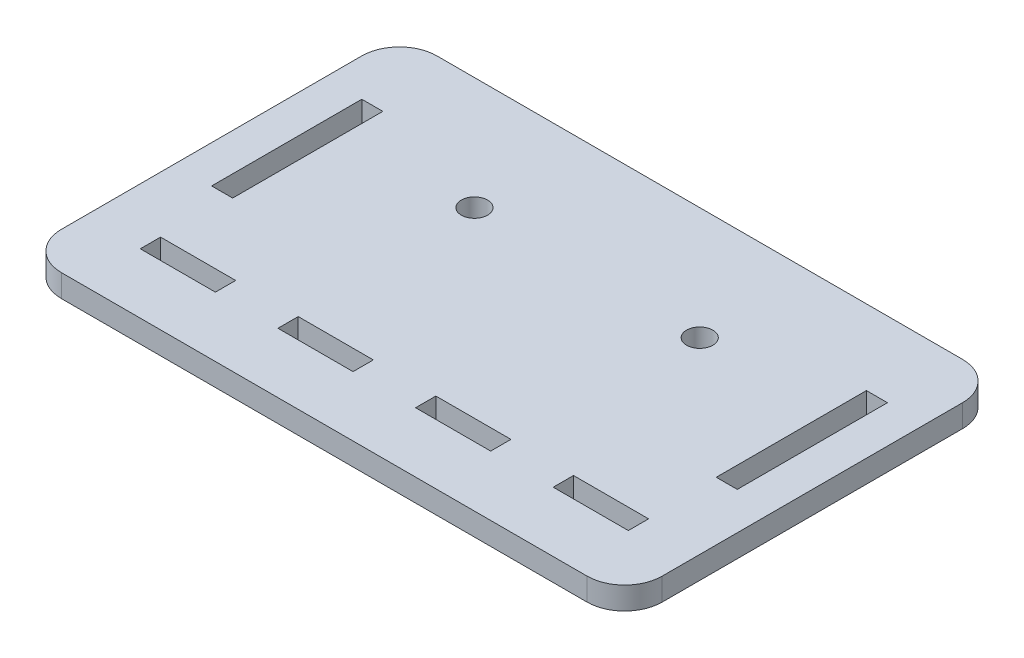
SolidWorks part; units mm, degrees
ref_plane "Front Plane" through (0, 0, 0) normal (0, 0, 1) x (1, 0, 0)
ref_plane "Top Plane" through (0, 0, 0) normal (0, 1, 0) x (1, 0, 0)
ref_plane "Right Plane" through (0, 0, 0) normal (1, 0, 0) x (0, 0, -1)
sketch "Sketch1" plane through (0, 0, 0) normal (0, 1, 0) x (1, 0, 0)
  line L0 (0, 35.9833) -> (0, -46.6527) construction
  line L1 (40, 25) -> (-40, 25)
  line L2 (-40, 25) -> (-40, -25)
  line L3 (-40, -25) -> (40, -25)
  line L4 (40, 25) -> (40, -25)
  line L5 (-32.5, -17) -> (32.5, -17) construction
  line L6 (-14.17, -14.3) -> (-4.17, -14.3)
  line L7 (-32.5, -17) -> (-22.5, -17)
  line L8 (-32.5, -17) -> (-32.5, -14.3)
  line L9 (-32.5, -14.3) -> (-22.5, -14.3)
  line L10 (-22.5, -17) -> (-22.5, -14.3)
  line L11 (-14.17, -17) -> (-4.17, -17)
  line L12 (-4.17, -17) -> (-4.17, -14.3)
  line L13 (-14.17, -17) -> (-14.17, -14.3)
  line L14 (4.16, -14.3) -> (14.16, -14.3)
  line L15 (4.16, -17) -> (14.16, -17)
  line L16 (14.16, -17) -> (14.16, -14.3)
  line L17 (4.16, -17) -> (4.16, -14.3)
  line L18 (22.49, -14.3) -> (32.49, -14.3)
  line L19 (22.49, -17) -> (32.49, -17)
  line L20 (32.49, -17) -> (32.49, -14.3)
  line L21 (22.49, -17) -> (22.49, -14.3)
  line L22 (-32.2, 15) -> (-32.2, -5)
  line L23 (35, 15) -> (32.2, 15)
  line L24 (35, 15) -> (35, -5)
  line L25 (35, -5) -> (32.2, -5)
  line L26 (32.2, 15) -> (32.2, -5)
  line L27 (-35, -5) -> (-32.2, -5)
  line L28 (-35, 15) -> (-35, -5)
  line L29 (-35, 15) -> (-32.2, 15)
  point P8 (0, -25)
  point P9 (0, 25)
  dimension "D1" = 50
  dimension "D2" = 40
  dimension "D3" = 25
  dimension "D4" = 65
  dimension "D5" = 32.5
  dimension "D6" = 8
  dimension "D7" = 2.7
  dimension "D8" = 10
  dimension "D10" = 20
  dimension "D11" = 10
  dimension "D12" = 2.8
  dimension "D13" = 5
  dimension "D9" = 4
extrude "Boss-Extrude1" add sketch "Sketch1" along normal blind 3
sketch "Sketch2" plane through (0, 3, 0) normal (0, 1, 0) x (1, 0, 0)
  circle A0 centre (15, 10) radius 1.75
  circle A1 centre (-15, 10) radius 1.75
  dimension "D1" = 3.5
  dimension "D4" = 2
  dimension "D2" = 10
  dimension "D3" = 15
extrude "Cut-Extrude1" cut sketch "Sketch2" against normal blind 3
fillet "Fillet1" radius 5 4 edges at (40, 1.5, 25) (-40, 1.5, 25) (-40, 1.5, -25) (40, 1.5, -25)
